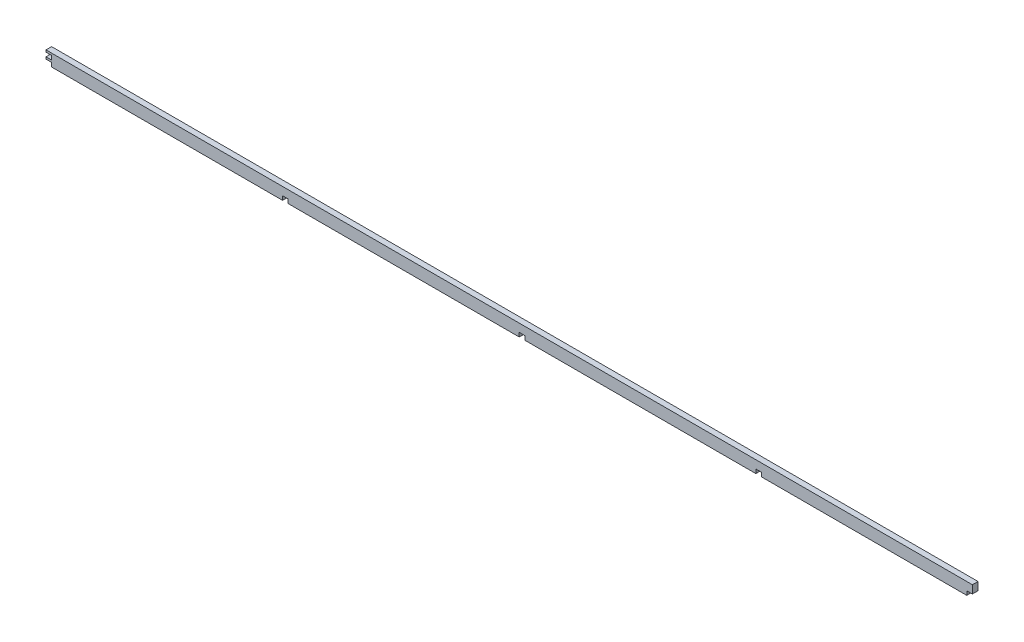
SolidWorks part; units mm, degrees
material "Фанера"
ref_plane "Front Plane" through (0, 0, 0) normal (0, 0, 1) x (1, 0, 0)
ref_plane "Top Plane" through (0, 0, 0) normal (0, 1, 0) x (1, 0, 0)
ref_plane "Right Plane" through (0, 0, 0) normal (1, 0, 0) x (0, 0, -1)
sketch "Эскиз2" plane through (0, 0, 0) normal (0, 0, 1) x (1, 0, 0)
  line L0 (-114.2, 16.0584) -> (-114.2, -22.9321) construction
  line L1 (-229.2, -3) -> (-114.2, -3)
  line L2 (-229.2, -3) -> (-229.2, -1)
  line L3 (-229.2, 3) -> (229.2, 3)
  line L4 (229.2, -1) -> (229.2, 3)
  line L5 (-229.2, -3) -> (229.2, 3) construction
  line L6 (-229.2, 3) -> (226.4, -2.9634) construction
  line L7 (-229.2, 2) -> (-232, 2)
  line L10 (-232, 2) -> (-232, 3)
  line L11 (-111.4, 12.1277) -> (-111.4, -19.9797) construction
  line L12 (-232, 3) -> (-229.2, 3)
  line L13 (-233.0787, 1) -> (-225.558, 1) construction
  line L14 (-232, -1) -> (-229.2, -1)
  line L15 (-229.2, 0) -> (-232, 0)
  line L16 (-232, 0) -> (-232, -1)
  line L17 (-229.2, 0) -> (-229.2, 2)
  line L18 (3.6, 14.8857) -> (3.6, -40.87) construction
  line L19 (6.4, 14.8857) -> (6.4, -40.87) construction
  line L20 (-114.2, -3) -> (-114.2, -1)
  line L21 (-114.2, -1) -> (-111.4, -1)
  line L22 (-111.4, -1) -> (-111.4, -3)
  line L23 (-111.4, -3) -> (3.6, -3)
  line L24 (3.6, -3) -> (3.6, -1)
  line L25 (3.6, -1) -> (6.4, -1)
  line L26 (6.4, -1) -> (6.4, -3)
  line L27 (6.4, -3) -> (121.4, -3)
  line L28 (226.4, -3) -> (226.4, -1)
  line L29 (226.4, -1) -> (229.2, -1)
  line L30 (121.4, 23.391) -> (121.4, -18.6675) construction
  line L31 (124.2, 23.391) -> (124.2, -15.4674) construction
  line L32 (121.4, -3) -> (121.4, -1)
  line L33 (121.4, -1) -> (124.2, -1)
  line L34 (124.2, -1) -> (124.2, -3)
  line L35 (124.2, -3) -> (226.4, -3)
  point P0 (0, 0)
  point P38 (121.4, -3)
  point P39 (124.2, -3)
  dimension "D1" = 458.4
  dimension "D2" = 6
  dimension "D3" = 1
  dimension "D4" = 2.8
  dimension "D5" = 2
  dimension "D6" = 115
  dimension "D7" = 2.8
  dimension "D8" = 115
  dimension "D9" = 2.8
  dimension "D10" = 4
  dimension "D11" = 4
  dimension "D12" = 4
  dimension "D13" = 2.8
  dimension "D14" = 2.8
  dimension "D15" = 115
  dimension "D16" = 4
extrude "Бобышка-Вытянуть1" add sketch "Эскиз2" along normal mid plane 2.8
